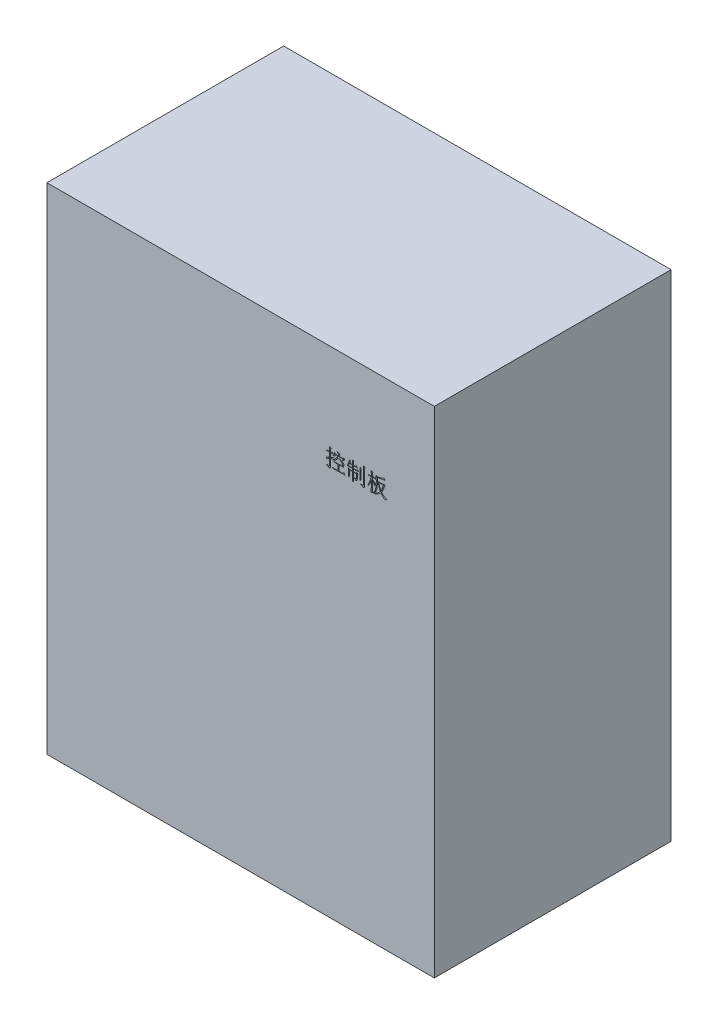
SolidWorks part; units mm, degrees
ref_plane "前视基准面" through (0, 0, 0) normal (0, 0, 1) x (1, 0, 0)
ref_plane "上视基准面" through (0, 0, 0) normal (0, 1, 0) x (1, 0, 0)
ref_plane "右视基准面" through (0, 0, 0) normal (1, 0, 0) x (0, 0, -1)
sketch "草图1" plane through (0, 0, 0) normal (0, 0, 1) x (1, 0, 0)
  line L1 (22.6768, 61.2753) -> (112.6768, 61.2753)
  line L2 (22.6768, 61.2753) -> (22.6768, -53.7247)
  line L3 (22.6768, -53.7247) -> (112.6768, -53.7247)
  line L4 (112.6768, 61.2753) -> (112.6768, -53.7247)
  dimension "D1" = 115
  dimension "D2" = 90
extrude "凸台-拉伸1" add sketch "草图1" along normal blind 55
sketch "草图2" plane through (0, 0, 55) normal (0, 0, 1) x (1, 0, 0)
  text T0 "控制板"
extrude "切除-拉伸1" cut sketch "草图2" against normal blind 2
